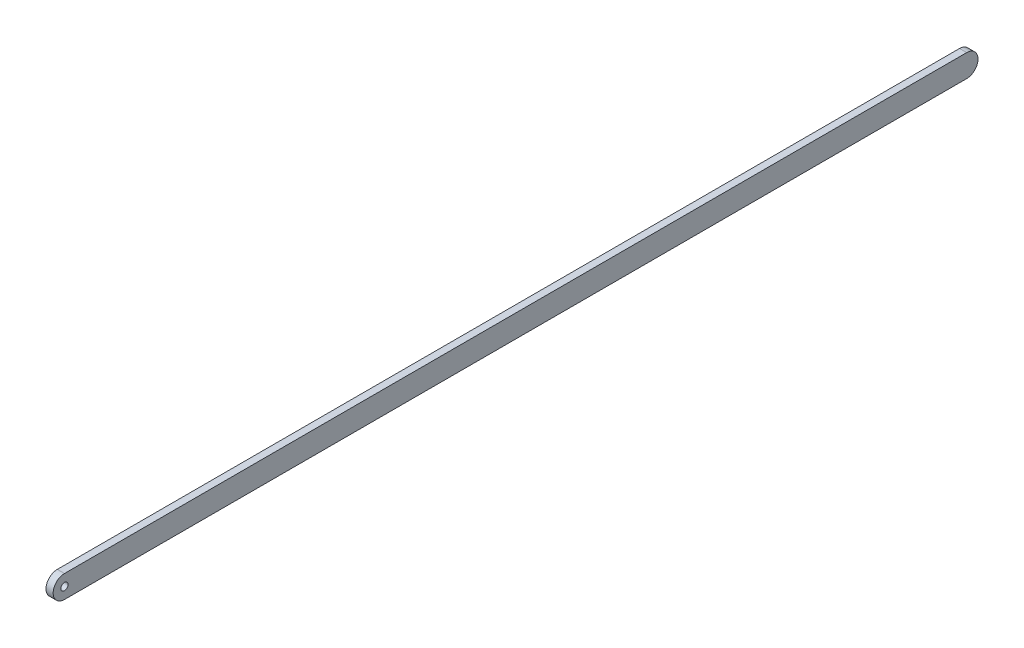
SolidWorks part; units mm, degrees
ref_plane "Front Plane" through (0, 0, 0) normal (0, 0, 1) x (1, 0, 0)
ref_plane "Top Plane" through (0, 0, 0) normal (0, 1, 0) x (1, 0, 0)
ref_plane "Right Plane" through (0, 0, 0) normal (1, 0, 0) x (0, 0, -1)
sketch "Sketch1" plane through (0, 0, 0) normal (1, 0, 0) x (0, 0, -1)
  line L0 (-200, 0) -> (200, 0) construction
  line L1 (-200, 5) -> (200, 5)
  line L2 (-200, -5) -> (200, -5)
  arc A0 (-200, 5) -> (-200, -5) centre (-200, 0) ccw
  arc A1 (200, -5) -> (200, 5) centre (200, 0) ccw
  point P2 (0, 0)
  dimension "D1" = 5
  dimension "D2" = 400
extrude "Boss-Extrude1" add sketch "Sketch1" along normal blind 3.175
hole_wizard "M3 Clearance Hole1" positions "Sketch3" profile "Sketch4" hole size "M3" standard "ANSI Metric"
sketch "Sketch3" plane through (3.175, 0, 0) normal (1, 0, 0) x (0, 0, -1)
  arc A0 (-200, 5) -> (-200, -5) centre (-200, 0) ccw construction
  point P0 (-200, 0)
  point P3 (0, 0)
sketch "Sketch4" plane through (3.175, 0, 200) normal (0, 1, 0) x (0, 0, -1)
  line L0 (0, 0) -> (0, 4)
  line L1 (0, 4) -> (1.6, 3.0386)
  line L2 (1.6, 3.0386) -> (1.6, 0)
  line L5 (1.6, 0) -> (0, 0)
  line L10 (0, 4) -> (-1.6, 3.0386) construction
  line L11 (0, -6.35) -> (0, 107.95) construction
  dimension "Hole Dia." = 3.2
  dimension "Hole Depth" = 4
  dimension "Drill Angle" = 118
